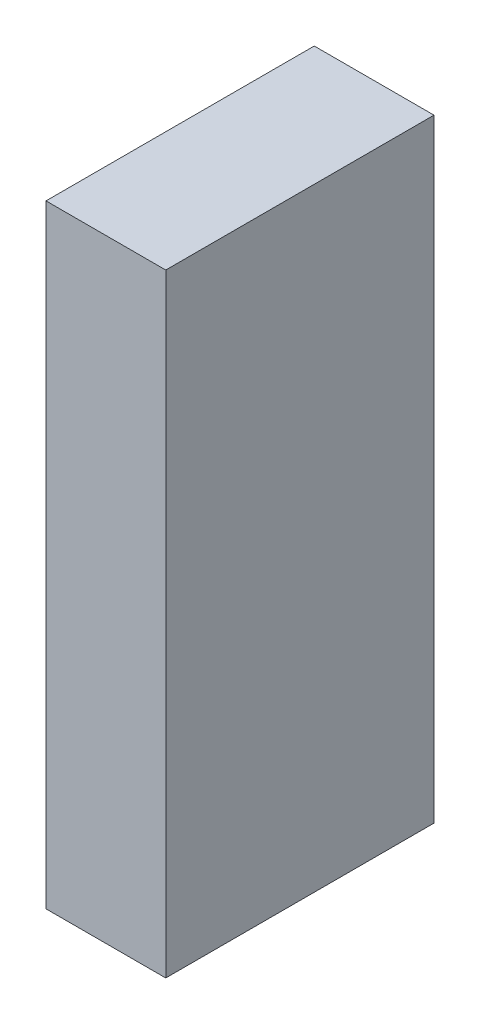
SolidWorks part; units mm, degrees
ref_plane "Front Plane" through (0, 0, 0) normal (0, 0, 1) x (1, 0, 0)
ref_plane "Top Plane" through (0, 0, 0) normal (0, 1, 0) x (1, 0, 0)
ref_plane "Right Plane" through (0, 0, 0) normal (1, 0, 0) x (0, 0, -1)
sketch "Sketch1" plane through (0, 0, 0) normal (0, 1, 0) x (1, 0, 0)
  line L1 (12.5, -28) -> (-12.5, -28)
  line L2 (12.5, -28) -> (12.5, 28)
  line L3 (12.5, 28) -> (-12.5, 28)
  line L4 (-12.5, -28) -> (-12.5, 28)
  line L5 (12.5, -28) -> (-12.5, 28) construction
  line L6 (12.5, 28) -> (-12.5, -28) construction
  point P0 (0, 0)
  dimension "D1" = 56
  dimension "D2" = 25
extrude "Boss-Extrude1" add sketch "Sketch1" along normal blind 128
